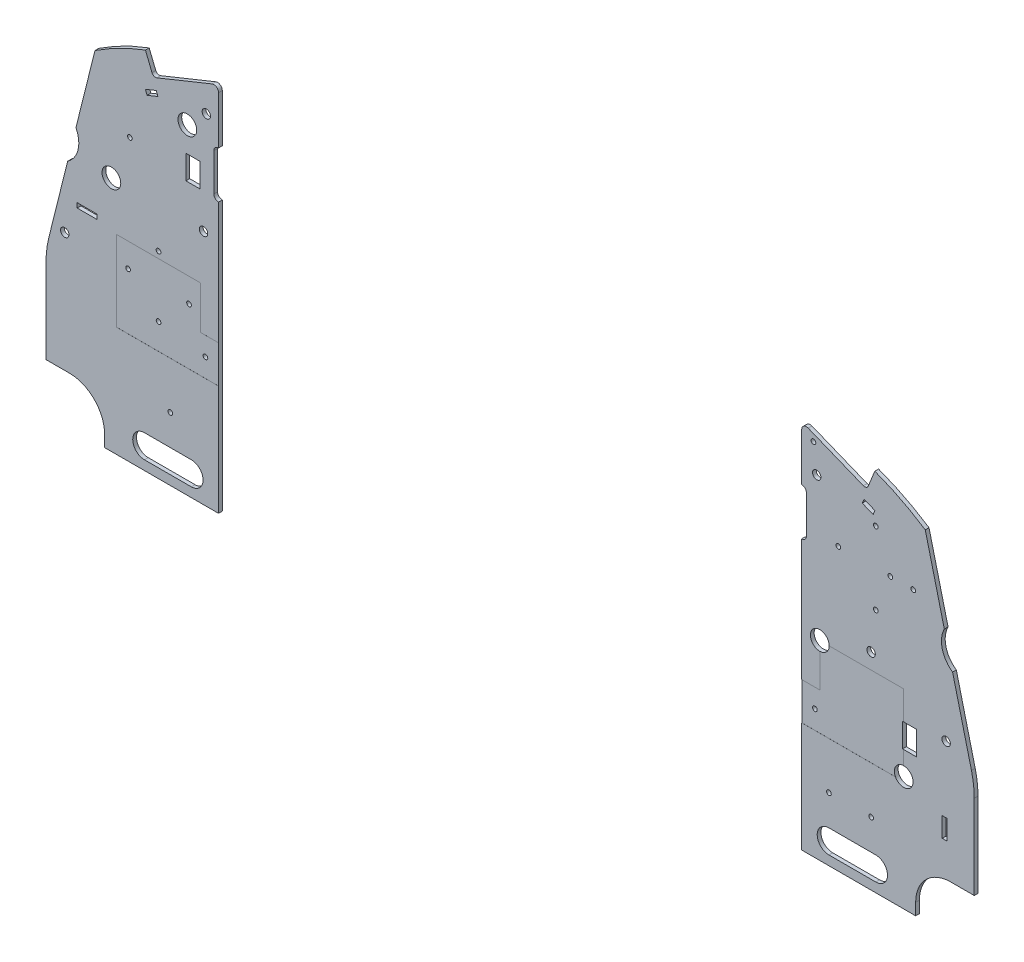
SolidWorks part; units mm, degrees
ref_plane "Ebene vorne" through (0, 0, 0) normal (0, 0, 1) x (1, 0, 0)
ref_plane "Ebene oben" through (0, 0, 0) normal (0, 1, 0) x (1, 0, 0)
ref_plane "Ebene rechts" through (0, 0, 0) normal (1, 0, 0) x (0, 0, -1)
ref_plane "Ebene1" through (0, 0, 13.9) normal (0, 0, 1) x (1, 0, 0)
sketch "Skizze2" plane through (0, 0, 13.9) normal (0, 0, 1) x (1, 0, 0)
  line L1 (-94, 14.5) -> (-99, 14.5)
  line L10 (-62.2, 4.5) -> (-62.2, 83.6937)
  line L30 (-88.5537, 76.827) -> (-99, 34.9291)
  line L32 (-77.7903, 82.2888) -> (-76.0905, 78.0816)
  line L33 (-76.0905, 78.0816) -> (-62.2, 83.6937)
  line L36 (-86.5, 4.5) -> (-62.2, 4.5)
  line L37 (-86.5, 7) -> (-86.5, 4.5)
  line L38 (-99, 34.9291) -> (-99, 14.5)
  arc A0 (-88.5537, 76.827) -> (-77.7903, 82.2888) centre (-59.8, 33.5) cw
  arc A1 (-86.5, 7) -> (-94, 14.5) centre (-94, 7) ccw
  dimension "D7" = 52
  dimension "D11" = 7.5
  dimension "D1" = 62.2
  dimension "D2" = 104.5094
  dimension "D3" = 99
  dimension "D4" = 94
  dimension "D5" = 14
  dimension "D6" = 68
  dimension "D8" = 59.8
  dimension "D9" = 33.5
  dimension "D10" = 7
  dimension "D12" = 100.9
  dimension "D13" = 41.3
  dimension "D14" = 4.5
extrude "Aufsatz-Linear austragen1" add sketch "Skizze2" against normal blind 0.8
fillet "Verrundung1" radius 20 1 edges at (-99, 34.9291, 13.5)
fillet "Verrundung3" radius 1 1 edges at (-62.2, 83.6937, 13.5)
sketch "Skizze4" plane through (0, 0, 13.9) normal (0, 0, 1) x (1, 0, 0)
  circle A0 centre (-97.5, 58) radius 5.5
  dimension "D1" = 11
  dimension "D2" = 58
  dimension "D3" = 97.5
extrude "Schnitt-Linear austragen2" cut sketch "Skizze4" against normal through all
sketch "Skizze5" plane through (0, 0, 13.9) normal (0, 0, 1) x (1, 0, 0)
  line L0 (-62.2, 63) -> (-62.2, 71) construction
  line L1 (-63.2, 63) -> (-63.2, 71)
  line L2 (-61.2, 63) -> (-61.2, 71)
  line L3 (-78, 9) -> (-68, 9) construction
  line L4 (-62.2, 4.5) -> (-62.2, 82.2112) construction
  line L5 (-64, 33.75) -> (-66, 33.75) construction
  line L6 (-64, 33.75) -> (-64, 30.25) construction
  line L7 (-64, 30.25) -> (-66, 30.25) construction
  line L8 (-66, 33.75) -> (-66, 30.25) construction
  line L9 (-78, 11.5) -> (-68, 11.5)
  line L10 (-78, 6.5) -> (-68, 6.5)
  line L11 (-77.809, 75.0317) -> (-77.4344, 74.1046)
  line L12 (-77.4344, 74.1046) -> (-75.1164, 75.0411)
  line L13 (-75.1164, 75.0411) -> (-75.491, 75.9683)
  line L14 (-75.491, 75.9683) -> (-77.809, 75.0317)
  line L15 (0, -16.4542) -> (0, 99.0178) construction
  arc A0 (-63.2, 63) -> (-61.2, 63) centre (-62.2, 63) ccw
  arc A1 (-61.2, 71) -> (-63.2, 71) centre (-62.2, 71) ccw
  circle A2 centre (-65, 32) radius 0.5
  circle A3 centre (-81.1, 64.5) radius 0.5
  arc A4 (-78, 11.5) -> (-78, 6.5) centre (-78, 9) ccw
  arc A5 (-68, 6.5) -> (-68, 11.5) centre (-68, 9) ccw
  point P2 (-62.2, 67)
  point P17 (-65, 33.75)
  point P18 (-64, 32)
  point P28 (-76.65, 75.5)
  point P29 (-73, 9)
  dimension "D3" = 1
  dimension "D8" = 1
  dimension "D14" = 1
  dimension "D17" = 2.5
  dimension "D1" = 71
  dimension "D2" = 63
  dimension "D4" = 2
  dimension "D5" = 3.5
  dimension "D6" = 65
  dimension "D7" = 32
  dimension "D9" = 22
  dimension "D10" = 75.5
  dimension "D11" = 76.65
  dimension "D12" = 1
  dimension "D13" = 2.5
  dimension "D15" = 64.5
  dimension "D16" = 81.1
  dimension "D18" = 9
  dimension "D19" = 10
  dimension "D20" = 73
extrude "Schnitt-Linear austragen3" cut sketch "Skizze5" against normal through all both and the other way through all
fillet "Verrundung4" radius 0.8 1 edges at (-76.0905, 78.0816, 13.5)
mirror "Spiegeln1" about plane through (0, 0, 0) normal (1, 0, 0) of bodies 108 102
sketch "Skizze3" plane through (0, 0, 13.9) normal (0, 0, 1) x (1, 0, 0)
  line L0 (-69.15, 67.55) -> (-66.15, 67.55)
  line L1 (-92.35, 45.827) -> (-88.1471, 45.827)
  line L2 (-92.35, 45.827) -> (-92.35, 46.827)
  line L3 (-92.35, 46.827) -> (-88.1471, 46.827)
  line L4 (-88.1471, 45.827) -> (-88.1471, 46.827)
  line L5 (93.1721, 21.65) -> (92.1721, 21.65)
  line L6 (93.1721, 21.65) -> (93.1721, 25.8513)
  line L7 (93.1721, 25.8513) -> (92.1721, 25.8513)
  line L8 (92.1721, 21.65) -> (92.1721, 25.8513)
  line L9 (83.7, 39.05) -> (86.7, 39.05)
  line L10 (83.7, 39.05) -> (83.7, 33.95)
  line L11 (83.7, 33.95) -> (86.7, 33.95)
  line L12 (86.7, 39.05) -> (86.7, 33.95)
  line L13 (-69.15, 67.55) -> (-69.15, 62.45)
  line L14 (-69.15, 62.45) -> (-66.15, 62.45)
  line L15 (-66.15, 67.55) -> (-66.15, 62.45)
  circle A0 centre (-64.8, 77) radius 0.9
  circle A1 centre (-68.85, 72.95) radius 2
  circle A2 centre (-85.05, 55.05) radius 2
  circle A3 centre (-65.4, 55) radius 0.9
  circle A5 centre (-95, 40) radius 0.9
  circle A6 centre (65.4, 75.4) radius 0.9
  circle A7 centre (77, 48.5) radius 0.9
  circle A8 centre (66.05, 45.15) radius 2
  circle A9 centre (83.95, 28.95) radius 2
  circle A10 centre (93, 40) radius 0.9
  circle A11 centre (64.7, 81.2) radius 0.5
  circle A12 centre (78, 72.25) radius 0.5
  circle A13 centre (86, 64.5) radius 0.5
  circle A14 centre (70, 64.5) radius 0.5
  circle A15 centre (78, 56.75) radius 0.5
  circle A16 centre (68, 18) radius 0.5
  circle A17 centre (77, 18) radius 0.5
  circle A18 centre (-72.5, 18) radius 0.5
  circle A19 centre (-75, 33.5272) radius 0.5
  circle A20 centre (-81.5, 40.0272) radius 0.5
  circle A21 centre (-68.5, 40.0272) radius 0.5
  circle A22 centre (-75, 46.5272) radius 0.5
  point P61 (86.7, 36.5)
  point P62 (-69.15, 65)
  point P63 (-67.65, 62.45)
  point P65 (85.2, 33.95)
  dimension "D1" = 4
  dimension "D2" = 1.8
  dimension "D3" = 1
  dimension "D4" = 1
  dimension "D5" = 3
  dimension "D6" = 5.1
  dimension "D7" = 67.65
  dimension "D8" = 36.5
  dimension "D9" = 85.2
  dimension "D10" = 65
extrude "Schnitt-Linear austragen1" cut sketch "Skizze3" against normal through all
sketch "Skizze6" plane through (0, 0, 13.9) normal (0, 0, 1) x (1, 0, 0)
  line L0 (83.9434, 45.15) -> (83.9434, 28.0122)
  line L1 (83.9434, 28.0122) -> (54.6502, 28.0122)
  line L2 (54.6502, 28.0122) -> (54.6502, 36.0009)
  line L3 (54.6502, 36.0009) -> (66.05, 36.0009)
  line L4 (66.05, 36.0009) -> (66.05, 45.15)
  line L5 (66.05, 45.15) -> (83.9434, 45.15)
  line L6 (0, 120.3191) -> (0, -54.2742) construction
  line L11 (-66.05, 45.15) -> (-83.9434, 45.15)
  line L12 (-66.05, 36.0009) -> (-66.05, 45.15)
  line L13 (-54.6502, 36.0009) -> (-66.05, 36.0009)
  line L14 (-54.6502, 28.0122) -> (-54.6502, 36.0009)
  line L15 (-83.9434, 28.0122) -> (-54.6502, 28.0122)
  line L16 (-83.9434, 45.15) -> (-83.9434, 28.0122)
extrude "Schnitt-Linear austragen4" cut sketch "Skizze6" against normal blind 0.01
